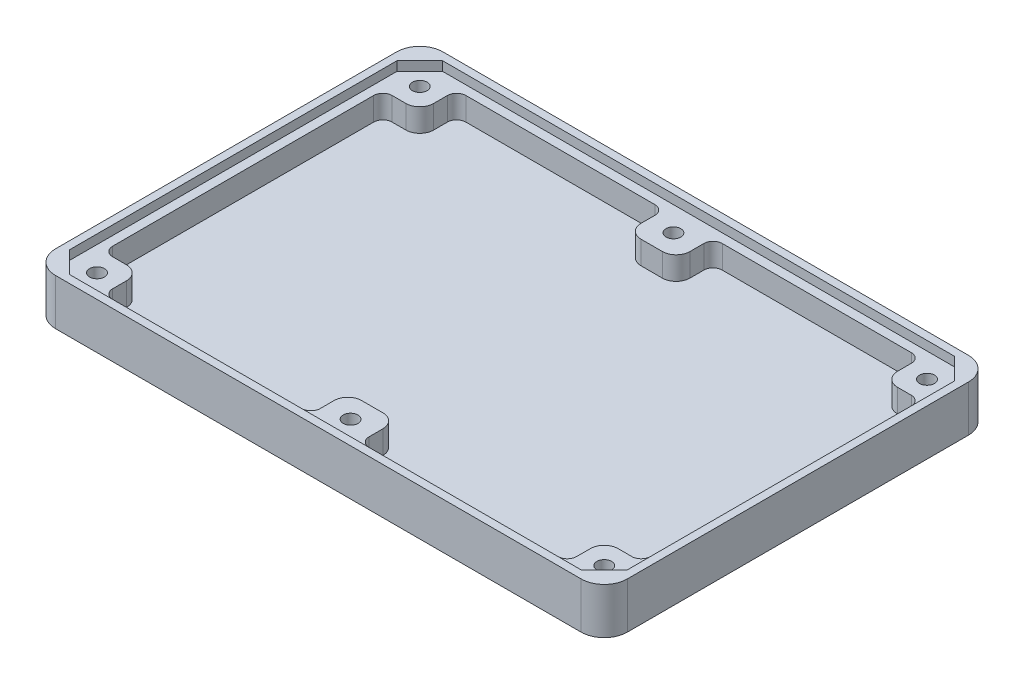
SolidWorks part; units mm, degrees
ref_plane "Front Plane" through (0, 0, 0) normal (0, 0, 1) x (1, 0, 0)
ref_plane "Top Plane" through (0, 0, 0) normal (0, 1, 0) x (1, 0, 0)
ref_plane "Right Plane" through (0, 0, 0) normal (1, 0, 0) x (0, 0, -1)
sketch "Sketch1" plane through (0, 0, 0) normal (0, 1, 0) x (1, 0, 0)
  line L1 (-221.313, -1.9404) -> (-97.313, -1.9404)
  line L2 (-221.313, -1.9404) -> (-221.313, -85.9404)
  line L3 (-221.313, -85.9404) -> (-97.313, -85.9404)
  line L4 (-97.313, -1.9404) -> (-97.313, -85.9404)
  dimension "D1" = 124
  dimension "D2" = 84
extrude "Boss-Extrude1" add sketch "Sketch1" along normal blind 10
sketch "Sketch2" plane through (0, 10, 0) normal (0, 1, 0) x (1, 0, 0)
  line L0 (-214.6632, -3.6404) -> (-219.613, -8.5901)
  line L1 (-219.613, -8.5901) -> (-219.613, -79.5901)
  line L2 (-219.613, -79.5901) -> (-214.9627, -84.2404)
  line L3 (-214.9627, -84.2404) -> (-103.9627, -84.2404)
  line L4 (-103.9627, -84.2404) -> (-99.013, -79.2906)
  line L5 (-99.013, -79.2906) -> (-99.013, -8.2906)
  line L6 (-99.013, -8.2906) -> (-103.6632, -3.6404)
  line L7 (-103.6632, -3.6404) -> (-214.6632, -3.6404)
  line L8 (-214.313, -3.9404) -> (-149.313, -3.9404) construction
  line L11 (-99.313, -8.9404) -> (-99.313, -78.9404) construction
  line L12 (-219.313, -8.9404) -> (-219.313, -78.9404) construction
  line L13 (-214.313, -83.9404) -> (-149.313, -83.9404) construction
  dimension "D1" = 0.3
  dimension "D2" = 0.3
  dimension "D3" = 135
  dimension "D4" = 111
  dimension "D5" = 0.3
  dimension "D6" = 71
  dimension "D7" = 0.3
  dimension "D8" = 7
  dimension "D9" = 7
extrude "Cut-Extrude1" cut sketch "Sketch2" against normal blind 2
sketch "Sketch3" plane through (0, 8, 0) normal (0, 1, 0) x (1, 0, 0)
  line L0 (-219.613, -8.5901) -> (-219.613, -79.5901) construction
  line L1 (-219.613, -13.6404) -> (-99.013, -13.6404)
  line L2 (-219.613, -13.6404) -> (-219.613, -74.2404)
  line L3 (-219.613, -74.2404) -> (-99.013, -74.2404)
  line L4 (-99.013, -13.6404) -> (-99.013, -74.2404)
  line L5 (-99.013, -79.2906) -> (-99.013, -8.2906) construction
  line L6 (-214.9627, -84.2404) -> (-103.9627, -84.2404) construction
  line L7 (-103.6632, -3.6404) -> (-214.6632, -3.6404) construction
  dimension "D1" = 10
  dimension "D2" = 10
extrude "Cut-Extrude2" cut sketch "Sketch3" against normal blind 5
sketch "Sketch4" plane through (0, 8, 0) normal (0, 1, 0) x (1, 0, 0)
  line L0 (-99.013, -13.6404) -> (-219.613, -13.6404) construction
  line L1 (-209.613, -13.6404) -> (-164.613, -13.6404)
  line L2 (-209.613, -13.6404) -> (-209.613, -3.6404)
  line L3 (-209.613, -3.6404) -> (-164.613, -3.6404)
  line L4 (-164.613, -13.6404) -> (-164.613, -3.6404)
  line L5 (-103.6632, -3.6404) -> (-214.6632, -3.6404) construction
  line L6 (-214.9627, -84.2404) -> (-103.9627, -84.2404) construction
  line L7 (-154.013, -3.6404) -> (-109.013, -3.6404)
  line L8 (-154.013, -3.6404) -> (-154.013, -13.6404)
  line L9 (-154.013, -13.6404) -> (-109.013, -13.6404)
  line L10 (-109.013, -3.6404) -> (-109.013, -13.6404)
  line L11 (-109.013, -84.2404) -> (-154.013, -84.2404)
  line L12 (-109.013, -84.2404) -> (-109.013, -74.2404)
  line L13 (-109.013, -74.2404) -> (-154.013, -74.2404)
  line L14 (-154.013, -84.2404) -> (-154.013, -74.2404)
  line L15 (-219.613, -74.2404) -> (-99.013, -74.2404) construction
  line L16 (-219.613, -8.5901) -> (-219.613, -79.5901) construction
  line L17 (-209.613, -84.2404) -> (-164.613, -84.2404)
  line L18 (-209.613, -84.2404) -> (-209.613, -74.2404)
  line L19 (-209.613, -74.2404) -> (-164.613, -74.2404)
  line L20 (-164.613, -84.2404) -> (-164.613, -74.2404)
  line L21 (-99.013, -79.2906) -> (-99.013, -8.2906) construction
  dimension "D1" = 10
  dimension "D2" = 10
  dimension "D3" = 10
  dimension "D4" = 10
  dimension "D5" = 45
  dimension "D6" = 45
  dimension "D7" = 45
  dimension "D8" = 45
extrude "Cut-Extrude3" cut sketch "Sketch4" against normal blind 5
fillet "Fillet1" radius 3 8 edges at (-209.613, 5.5, 74.2404) (-164.613, 5.5, 74.2404) (-154.013, 5.5, 74.2404) (-109.013, 5.5, 74.2404) (-109.013, 5.5, 13.6404) (-154.013, 5.5, 13.6404) (-164.613, 5.5, 13.6404) (-209.613, 5.5, 13.6404)
fillet "Fillet2" radius 5 4 edges at (-97.313, 5, 1.9404) (-221.313, 5, 1.9404) (-97.313, 5, 85.9404) (-221.313, 5, 85.9404)
sketch "Sketch5" plane through (0, 8, 0) normal (0, 1, 0) x (1, 0, 0)
  circle A0 centre (-214.313, -8.9404) radius 1.6
  circle A1 centre (-159.313, -8.9404) radius 1.6
  circle A2 centre (-104.313, -8.9404) radius 1.6
  circle A3 centre (-104.313, -78.9404) radius 1.6
  circle A4 centre (-159.313, -78.9404) radius 1.6
  circle A5 centre (-214.313, -78.9404) radius 1.6
extrude "Cut-Extrude4" cut sketch "Sketch5" against normal through all
sketch "Sketch7" plane through (0, 0, 0) normal (0, -1, 0) x (1, 0, 0)
  line L1 (-101.513, 5.4404) -> (-107.113, 5.4404)
  line L2 (-101.513, 5.4404) -> (-101.513, 12.4404)
  line L3 (-101.513, 12.4404) -> (-107.113, 12.4404)
  line L4 (-107.113, 5.4404) -> (-107.113, 12.4404)
  line L5 (-156.513, 5.4404) -> (-162.113, 5.4404)
  line L6 (-156.513, 5.4404) -> (-156.513, 12.4404)
  line L7 (-156.513, 12.4404) -> (-162.113, 12.4404)
  line L8 (-162.113, 5.4404) -> (-162.113, 12.4404)
  line L9 (-211.513, 5.4404) -> (-217.113, 5.4404)
  line L10 (-211.513, 5.4404) -> (-211.513, 12.4404)
  line L11 (-211.513, 12.4404) -> (-217.113, 12.4404)
  line L12 (-217.113, 5.4404) -> (-217.113, 12.4404)
  line L13 (-211.513, 75.4404) -> (-217.113, 75.4404)
  line L14 (-211.513, 75.4404) -> (-211.513, 82.4404)
  line L15 (-211.513, 82.4404) -> (-217.113, 82.4404)
  line L16 (-217.113, 75.4404) -> (-217.113, 82.4404)
  line L17 (-156.513, 75.4404) -> (-162.113, 75.4404)
  line L18 (-156.513, 75.4404) -> (-156.513, 82.4404)
  line L19 (-156.513, 82.4404) -> (-162.113, 82.4404)
  line L20 (-162.113, 75.4404) -> (-162.113, 82.4404)
  line L21 (-101.513, 75.4404) -> (-107.113, 75.4404)
  line L22 (-101.513, 75.4404) -> (-101.513, 82.4404)
  line L23 (-101.513, 82.4404) -> (-107.113, 82.4404)
  line L24 (-107.113, 75.4404) -> (-107.113, 82.4404)
  circle A0 centre (-104.313, 8.9404) radius 1.6 construction
  circle A1 centre (-159.313, 8.9404) radius 1.6 construction
  circle A2 centre (-214.313, 8.9404) radius 1.6 construction
  circle A3 centre (-214.313, 78.9404) radius 1.6 construction
  circle A4 centre (-159.313, 78.9404) radius 1.6 construction
  circle A5 centre (-104.313, 78.9404) radius 1.6 construction
  dimension "D1" = 2.8
  dimension "D2" = 5.6
  dimension "D3" = 3.5
  dimension "D4" = 7
  dimension "D5" = 2.8
  dimension "D6" = 5.6
  dimension "D7" = 3.5
  dimension "D8" = 7
  dimension "D9" = 2.8
  dimension "D10" = 5.6
  dimension "D11" = 7
  dimension "D12" = 3.5
  dimension "D13" = 5.6
  dimension "D14" = 2.8
  dimension "D15" = 7
  dimension "D16" = 3.5
  dimension "D17" = 7
  dimension "D18" = 5.6
  dimension "D19" = 3.5
  dimension "D20" = 2.8
  dimension "D21" = 7
  dimension "D22" = 3.5
  dimension "D23" = 5.6
  dimension "D24" = 2.8
extrude "Cut-Extrude5" cut sketch "Sketch7" against normal blind 4
sketch "Sketch8" plane through (0, 8, 0) normal (0, 1, 0) x (1, 0, 0)
  line L0 (-209.613, -77.2404) -> (-209.613, -84.2404) construction
  line L1 (-109.013, -84.2404) -> (-209.613, -84.2404)
  line L2 (-109.013, -84.2404) -> (-109.013, -82.2404)
  line L3 (-109.013, -82.2404) -> (-209.613, -82.2404)
  line L4 (-209.613, -84.2404) -> (-209.613, -82.2404)
  line L5 (-212.613, -13.6404) -> (-219.613, -13.6404) construction
  line L6 (-219.613, -74.2404) -> (-217.613, -74.2404)
  line L7 (-219.613, -74.2404) -> (-219.613, -13.6404)
  line L8 (-219.613, -13.6404) -> (-217.613, -13.6404)
  line L9 (-217.613, -74.2404) -> (-217.613, -13.6404)
  line L10 (-109.013, -10.6404) -> (-109.013, -3.6404) construction
  line L11 (-209.613, -3.6404) -> (-109.013, -3.6404)
  line L12 (-209.613, -3.6404) -> (-209.613, -5.6404)
  line L13 (-209.613, -5.6404) -> (-109.013, -5.6404)
  line L14 (-109.013, -3.6404) -> (-109.013, -5.6404)
  line L15 (-106.013, -74.2404) -> (-99.013, -74.2404) construction
  line L16 (-99.013, -13.6404) -> (-101.013, -13.6404)
  line L17 (-99.013, -13.6404) -> (-99.013, -74.2404)
  line L18 (-99.013, -74.2404) -> (-101.013, -74.2404)
  line L19 (-101.013, -13.6404) -> (-101.013, -74.2404)
  dimension "D1" = 2
  dimension "D2" = 2
  dimension "D3" = 2
  dimension "D4" = 2
extrude "Boss-Extrude2" add sketch "Sketch8" against normal up to surface (5 mm away) up to face at (-159.313, 3, 43.9404)
fillet "Fillet3" radius 2 12 edges at (-101.013, 5.5, 13.6404) (-109.013, 5.5, 5.6404) (-164.613, 5.5, 5.6404) (-154.013, 5.5, 5.6404) (-209.613, 5.5, 5.6404) (-217.613, 5.5, 13.6404) (-217.613, 5.5, 74.2404) (-209.613, 5.5, 82.2404) (-154.013, 5.5, 82.2404) (-164.613, 5.5, 82.2404) (-109.013, 5.5, 82.2404) (-101.013, 5.5, 74.2404)
